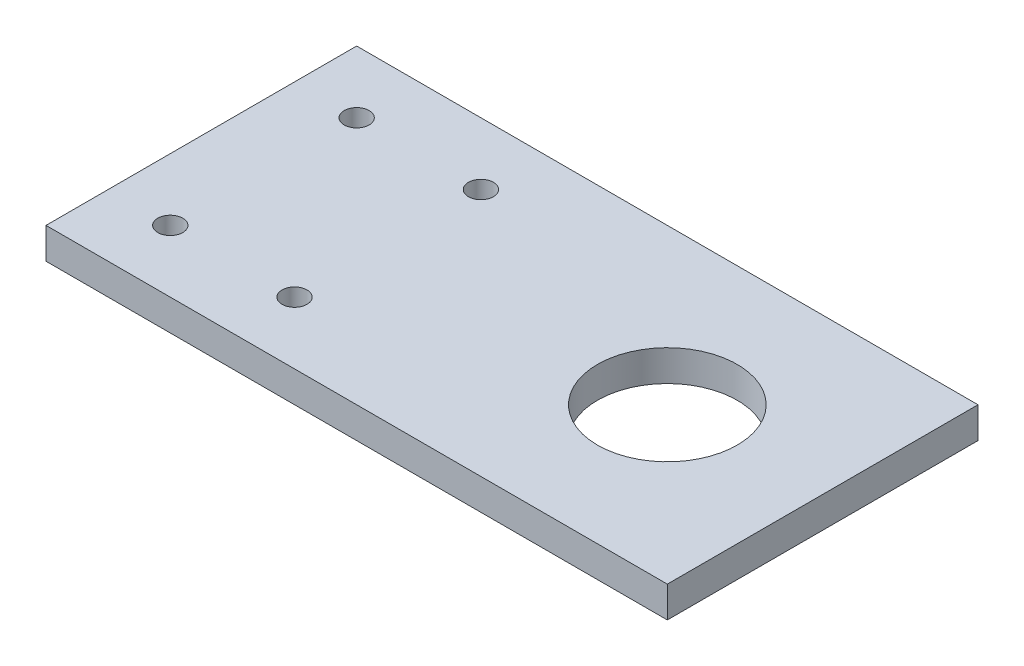
SolidWorks part; units mm, degrees
ref_plane "Front Plane" through (0, 0, 0) normal (0, 0, 1) x (1, 0, 0)
ref_plane "Top Plane" through (0, 0, 0) normal (0, 1, 0) x (1, 0, 0)
ref_plane "Right Plane" through (0, 0, 0) normal (1, 0, 0) x (0, 0, -1)
sketch "Sketch1" plane through (0, 0, 0) normal (0, 1, 0) x (1, 0, 0)
  line L0 (50.8, 31.75) -> (76.2, 31.75)
  line L1 (-50.8, -31.75) -> (50.8, -31.75)
  line L2 (-50.8, -31.75) -> (-50.8, 31.75)
  line L3 (-50.8, 31.75) -> (50.8, 31.75)
  line L5 (-50.8, -31.75) -> (50.8, 31.75) construction
  line L6 (-50.8, 31.75) -> (50.8, -31.75) construction
  line L7 (76.2, 31.75) -> (76.2, -31.75)
  line L8 (76.2, -31.75) -> (50.8, -31.75)
  point P0 (0, 0)
  dimension "D1" = 101.6
  dimension "D2" = 63.5
  dimension "D3" = 25.4
extrude "Boss-Extrude1" add sketch "Sketch1" along normal blind 6.35
sketch "Sketch2" plane through (0, 6.35, 0) normal (0, 1, 0) x (1, 0, 0)
  line L4 (76.2, 31.75) -> (-50.8, 31.75) construction
  line L5 (-50.8, -31.75) -> (76.2, -31.75) construction
  line L7 (0, 31.75) -> (0, -31.75) construction
  line L8 (-50.8, 31.75) -> (-50.8, -31.75) construction
  dimension "D1" = 50.8
hole_wizard "#10 Clearance Hole1" positions "Sketch3" profile "Sketch4" hole size "#10" standard "ANSI Inch" end condition through all
sketch "Sketch3" plane through (0, 6.35, 0) normal (0, 1, 0) x (1, 0, 0)
  line L4 (-38.1, 31.75) -> (-38.1, -31.75) construction
  line L5 (76.2, 31.75) -> (-50.8, 31.75) construction
  line L6 (-50.8, -31.75) -> (76.2, -31.75) construction
  line L8 (-12.7, 31.75) -> (-12.7, -31.75) construction
  line L9 (-50.8, 31.75) -> (-50.8, -31.75) construction
  line L11 (-50.8, 19.05) -> (0, 19.05) construction
  line L13 (-50.8, -19.05) -> (0, -19.05) construction
  point P0 (-38.1, 19.05)
  point P2 (-12.7, 19.05)
  point P4 (-12.7, -19.05)
  point P6 (-38.1, -19.05)
  dimension "D1" = 12.7
  dimension "D2" = 38.1
  dimension "D3" = 12.7
  dimension "D4" = 12.7
  dimension "D5" = 50.8
  dimension "D6" = 50.8
sketch "Sketch4" plane through (-38.1, 6.35, -19.05) normal (1, 0, 0) x (0, 0, 1)
  line L0 (0, 0) -> (0, 6.35)
  line L1 (0, 6.35) -> (2.5527, 6.35)
  line L2 (2.5527, 6.35) -> (2.5527, 0)
  line L5 (2.5527, 0) -> (0, 0)
  line L11 (0, -6.35) -> (0, 107.95) construction
  dimension "Thru Hole Dia." = 5.1054
  dimension "Thru Hole Depth" = 6.35
sketch "Sketch5" plane through (0, 6.35, 0) normal (0, 1, 0) x (1, 0, 0)
  line L0 (76.2, -31.75) -> (76.2, 31.75) construction
  line L3 (-50.8, -31.75) -> (76.2, -31.75) construction
  circle A1 centre (44.45, 0) radius 14.2875
  point P5 (44.45, 0)
  dimension "D3" = 28.575
  dimension "D1" = 31.75
  dimension "D2" = 31.75
extrude "Cut-Extrude1" cut sketch "Sketch5" against normal through all
